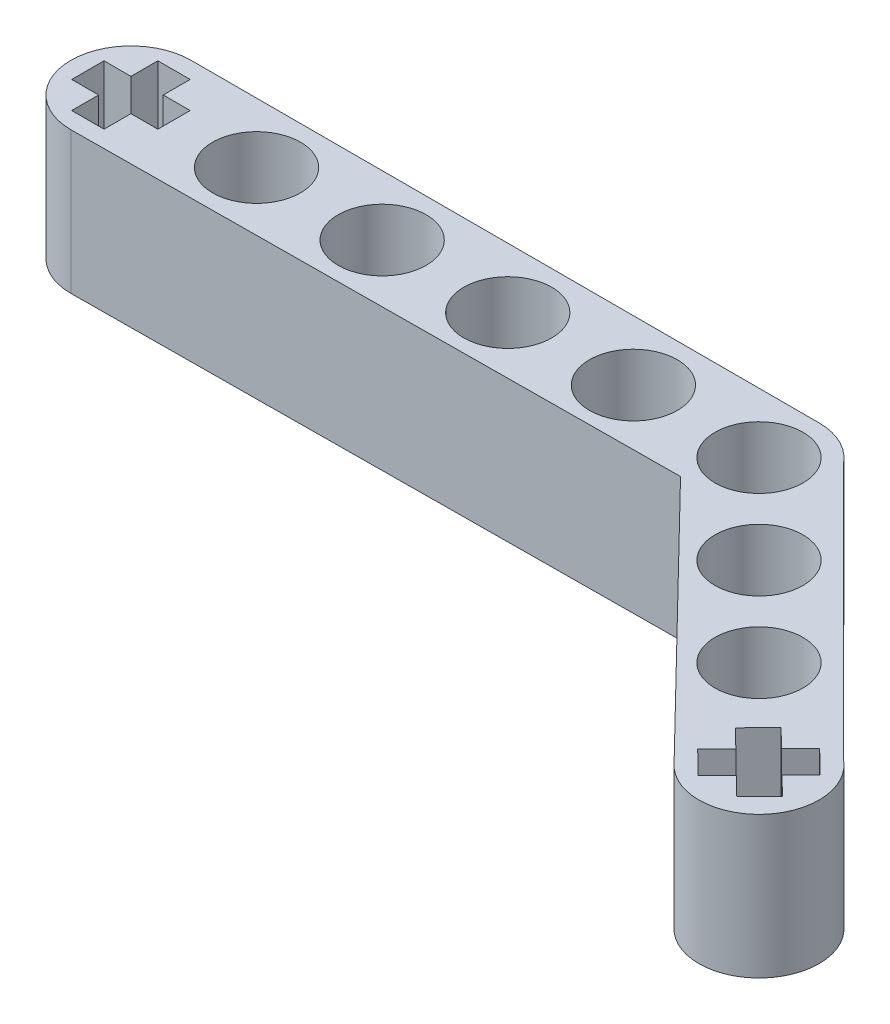
SolidWorks part; units mm, degrees
ref_plane "Front Plane" through (0, 0, 0) normal (0, 0, 1) x (1, 0, 0)
ref_plane "Top Plane" through (0, 0, 0) normal (0, 1, 0) x (1, 0, 0)
ref_plane "Right Plane" through (0, 0, 0) normal (1, 0, 0) x (0, 0, -1)
sketch "Sketch1" plane through (0, 0, 0) normal (0, 1, 0) x (1, 0, 0)
  line L0 (-2.85, 0) -> (31.35, 0) construction
  line L3 (35, 0) -> (49.8492, -14.8492)
  line L4 (37.5454, 2.178) -> (52.0272, -12.3039)
  line L5 (0, 3.35) -> (35, 3.35)
  line L7 (47.3538, -17.0843) -> (33.7262, -3.0984)
  line L9 (33.7262, -3.0984) -> (0, -3.35)
  circle A0 centre (0, 0) radius 2.45
  circle A1 centre (0, 0) radius 2.85
  circle A2 centre (7, 0) radius 2.85
  circle A3 centre (7, 0) radius 2.45
  circle A4 centre (14, 0) radius 2.85
  circle A5 centre (14, 0) radius 2.45
  circle A6 centre (21, 0) radius 2.85
  circle A7 centre (21, 0) radius 2.45
  circle A8 centre (28, 0) radius 2.85
  circle A9 centre (28, 0) radius 2.45
  circle A10 centre (35, 0) radius 2.85
  circle A11 centre (35, 0) radius 2.45
  circle A12 centre (39.9497, -4.9497) radius 2.85
  circle A13 centre (39.9497, -4.9497) radius 2.45
  circle A14 centre (44.8995, -9.8995) radius 2.85
  circle A15 centre (44.8995, -9.8995) radius 2.45
  circle A16 centre (49.8492, -14.8492) radius 2.85
  circle A17 centre (49.8492, -14.8492) radius 2.45
  circle A27 centre (0, 0) radius 3.35
  circle A28 centre (35, 0) radius 3.35
  arc A30 (37.5454, 2.178) -> (35, 3.35) centre (35, 0) ccw
  circle A31 centre (49.8492, -14.8492) radius 3.35
  arc A36 (42.3995, -2.6736) -> (42.3463, -2.6203) centre (40.1816, -4.8394) ccw
  dimension "D1" = 4.9
  dimension "D2" = 5.7
  dimension "D7" = 7
  dimension "D5" = 6.7
  dimension "D3" = 34.2
  dimension "D6" = 4
  dimension "D8" = 7
  dimension "D4" = 6
extrude "Boss-Extrude2" add sketch "Sketch1" along normal blind 7.9
sketch "Sketch2" plane through (0, 7.9, 0) normal (0, 1, 0) x (1, 0, 0)
  line L0 (0, -3.35) -> (0, 3.35) construction
  line L1 (0, 0) -> (-3.35, 0) construction
  line L2 (0, 0) -> (0, -2.4)
  line L3 (0, 0) -> (0, 2.4)
  line L4 (-0.9, 2.4) -> (0.9, 2.4)
  line L5 (-0.9, 2.4) -> (-0.9, 0.9)
  line L6 (0.9, 2.4) -> (0.9, 0.9)
  line L7 (-0.9, -2.4) -> (0.9, -2.4)
  line L8 (-0.9, -2.4) -> (-0.9, -0.9)
  line L9 (0.9, -2.4) -> (0.9, -0.9)
  line L10 (0, 0) -> (-2.4, 0)
  line L11 (-2.4, 0.9) -> (-2.4, -0.9)
  line L12 (-2.4, -0.9) -> (-0.9, -0.9)
  line L13 (-2.4, 0.9) -> (-0.9, 0.9)
  line L14 (2.4, -0.9) -> (0.9, -0.9)
  line L15 (2.4, 0.9) -> (2.4, -0.9)
  line L16 (2.4, 0.9) -> (0.9, 0.9)
  arc A0 (0, 3.35) -> (0, -3.35) centre (0, 0) ccw construction
  point P24 (-2.4, 0)
  dimension "D1" = 2.4
extrude "Cut-Extrude1" cut sketch "Sketch2" against normal up to surface (7.9 mm away) contours L15 L16 L6 L4 L3 L2 L7 L9 L14 | L13 L11 L10 L3 L4 L5 | L11 L12 L8 L7 L2 L10 up to face at (7, 0, 2.45)
sketch "Sketch3" plane through (0, 7.9, 0) normal (0, 1, 0) x (1, 0, 0)
  line L0 (47.3538, -17.0843) -> (52.0272, -12.3039) construction
  line L1 (47.1363, -12.1971) -> (52.2447, -17.1911) construction
  line L2 (51.3707, -12.9754) -> (48.0103, -16.4128)
  line L3 (48.0128, -13.0539) -> (51.3682, -16.3342)
  line L4 (47.3667, -15.7836) -> (48.6539, -17.0419)
  line L5 (47.3667, -15.7836) -> (50.7272, -12.3462)
  line L6 (48.6539, -17.0419) -> (52.0143, -13.6045)
  line L7 (50.7272, -12.3462) -> (52.0143, -13.6045)
  line L8 (51.9974, -15.6907) -> (50.7391, -16.9778)
  line L9 (50.7391, -16.9778) -> (47.3836, -13.6975)
  line L10 (51.9974, -15.6907) -> (48.6419, -12.4104)
  line L11 (48.6419, -12.4104) -> (47.3836, -13.6975)
  arc A0 (47.3538, -17.0843) -> (52.0272, -12.3039) centre (49.8492, -14.8492) ccw construction
  point P10 (49.6905, -14.6941)
  point P13 (49.6905, -14.6941)
  point P16 (49.6905, -14.6941)
  point P19 (48.0103, -16.4128)
  point P22 (50.3341, -15.3232)
  point P23 (49.047, -14.0649)
  point P26 (51.3682, -16.3342)
  point P30 (50.3197, -14.0505)
  point P31 (49.0614, -15.3376)
  dimension "D1" = 1.8
  dimension "D2" = 1.8
extrude "Cut-Extrude2" cut sketch "Sketch3" against normal up to surface (7.9 mm away) contours L6 L9 L2 L4 | L2 L9 L5 L4 | L9 L2 L3 L5 | L9 L6 L3 L2 | L9 L8 L3 L6 | L8 L10 L6 L3 | L6 L10 L2 L3 | L10 L6 L7 L2 | L10 L2 L7 L5 | L2 L10 L5 L3 | L10 L11 L3 L5 | L3 L11 L9 L5 up to face at (44.8995, 0, 12.3495)
